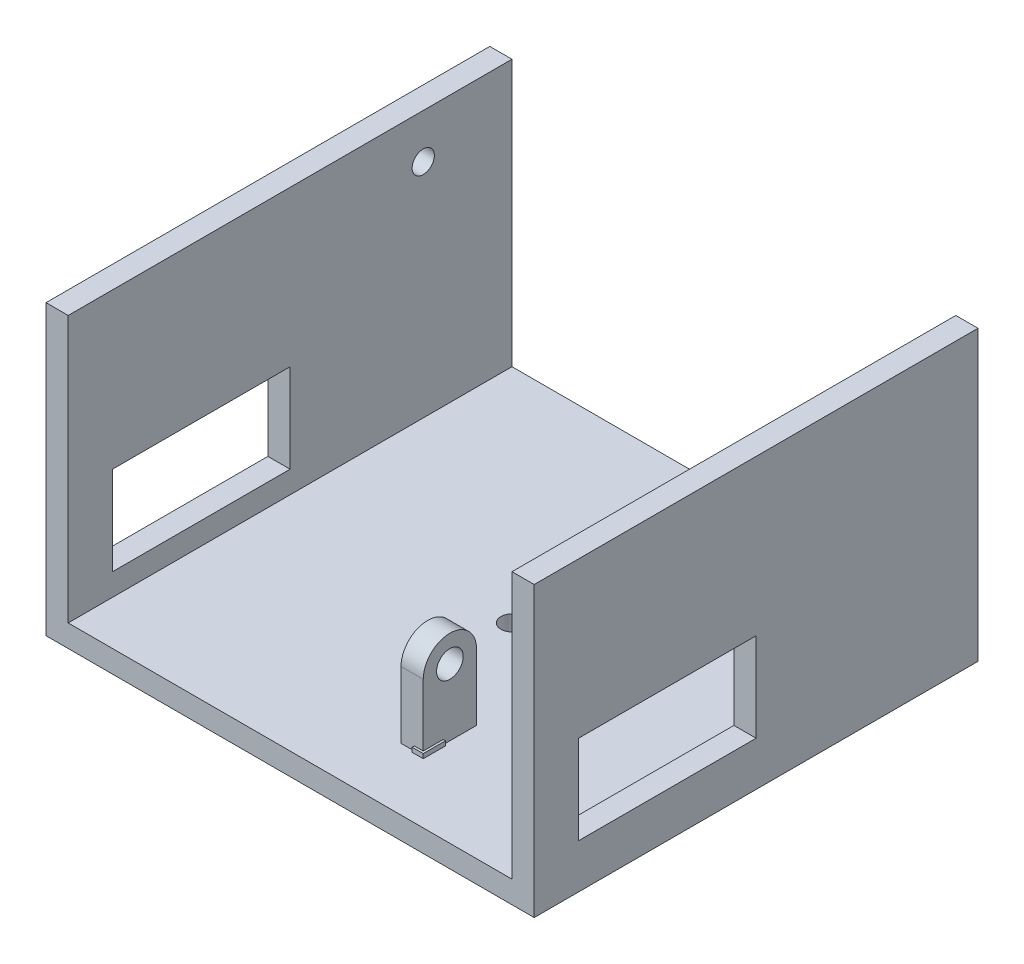
SolidWorks part; units mm, degrees
ref_plane "Front Plane" through (0, 0, 0) normal (0, 0, 1) x (1, 0, 0)
ref_plane "Top Plane" through (0, 0, 0) normal (0, 1, 0) x (1, 0, 0)
ref_plane "Right Plane" through (0, 0, 0) normal (1, 0, 0) x (0, 0, -1)
sketch "Sketch1" plane through (0, 0, 0) normal (0, 0, 1) x (1, 0, 0)
  line L0 (-50, 5) -> (50, 5)
  line L2 (55, 0) -> (-55, 0)
  line L7 (-55, 0) -> (-55, 65)
  line L8 (-55, 65) -> (-50, 65)
  line L9 (-50, 65) -> (-50, 5)
  line L10 (0, 0) -> (0, 425.5211) construction
  line L11 (50, 65) -> (50, 5)
  line L12 (55, 65) -> (50, 65)
  line L13 (55, 0) -> (55, 65)
  point P2 (0, 0)
  dimension "D1" = 60
  dimension "D2" = 5
  dimension "D3" = 110
  dimension "D4" = 5
extrude "Boss-Extrude2" add sketch "Sketch1" along normal blind 100
sketch "Sketch2" plane through (0, 5, 0) normal (0, 1, 0) x (1, 0, 0)
  line L0 (0, 0) -> (0, -100) construction
  line L1 (-29.4832, -50) -> (29.4832, -50) construction
  line L2 (50, -100) -> (-50, -100) construction
  circle A0 centre (0, -50) radius 2.5
  circle A4 centre (0, -30) radius 3
  point P9 (0, -50)
  dimension "D1" = 5
  dimension "D2" = 6
  dimension "D3" = 20
extrude "Cut-Extrude1" cut sketch "Sketch2" against normal blind 10
sketch "Sketch3" plane through (-55, 0, 0) normal (-1, 0, 0) x (0, 0, 1)
  line L0 (100, 0) -> (0, 0) construction
  line L1 (100, 65) -> (100, 0) construction
  line L2 (100, 65) -> (0, 65) construction
  line L3 (0, 65) -> (0, 0) construction
  circle A0 centre (80, 20) radius 2.5
  circle A1 centre (20, 55) radius 2.5
  dimension "D1" = 5
  dimension "D2" = 10
  dimension "D3" = 20
  dimension "D4" = 20
  dimension "D5" = 20
extrude "Cut-Extrude2" cut sketch "Sketch3" against normal blind 10
sketch "Sketch4" plane through (55, 0, 0) normal (1, 0, 0) x (0, 0, -1)
  line L0 (-100, 0) -> (0, 0) construction
  line L1 (-100, 0) -> (-100, 65) construction
  circle A0 centre (-80, 15) radius 2
  dimension "D1" = 4
  dimension "D2" = 15
  dimension "D3" = 20
extrude "Cut-Extrude3" cut sketch "Sketch4" against normal blind 10
sketch "Sketch5" plane through (-55, 0, 0) normal (-1, 0, 0) x (0, 0, 1)
  line L1 (90, 10) -> (50, 10)
  line L2 (90, 10) -> (90, 30)
  line L3 (90, 30) -> (50, 30)
  line L4 (50, 10) -> (50, 30)
  line L5 (90, 10) -> (50, 30) construction
  line L6 (90, 30) -> (50, 10) construction
  circle A0 centre (80, 20) radius 2.5 construction
  point P4 (70, 20)
  dimension "D3" = 10
  dimension "D4" = 10
  dimension "D1" = 20
  dimension "D2" = 40
extrude "Cut-Extrude4" cut sketch "Sketch5" against normal through all
sketch "Sketch6" plane through (0, 5, 0) normal (0, 1, 0) x (1, 0, 0)
  line L1 (11, -74) -> (16, -74)
  line L2 (11, -74) -> (11, -86)
  line L3 (11, -86) -> (16, -86)
  line L4 (16, -74) -> (16, -86)
  line L5 (11, -74) -> (16, -86) construction
  line L6 (11, -86) -> (16, -74) construction
  line L7 (50, -100) -> (50, 0) construction
  line L9 (50, -100) -> (-50, -100) construction
  point P0 (13.5, -80)
  dimension "D1" = 34
  dimension "D2" = 5
  dimension "D3" = 12
  dimension "D4" = 20
extrude "Boss-Extrude3" add sketch "Sketch6" along normal blind 15
sketch "Sketch8" plane through (11, 0, 0) normal (-1, 0, 0) x (0, 0, 1)
  line L1 (74, 20) -> (86, 20)
  arc A0 (74, 20) -> (86, 20) centre (80, 20) cw
extrude "Boss-Extrude4" add sketch "Sketch8" against normal up to surface (5 mm away) up to face at (16, 12.5, 80)
sketch "Sketch9" plane through (11, 0, 0) normal (-1, 0, 0) x (0, 0, 1)
  circle A0 centre (80, 20) radius 3
  dimension "D1" = 6
extrude "Cut-Extrude5" cut sketch "Sketch9" against normal blind 7
sketch "Sketch10" plane through (0, 5, 0) normal (0, 1, 0) x (1, 0, 0)
  line L0 (14, -86.5) -> (16.5, -86.5)
  line L1 (16.5, -86.5) -> (16.5, -81.5)
  line L2 (16.5, -81.5) -> (16, -81.5)
  line L4 (16, -81.5) -> (16, -86)
  line L5 (16, -86) -> (14, -86)
  line L7 (14, -86) -> (14, -86.5)
  line L8 (50, -100) -> (-50, -100) construction
  line L9 (50, -100) -> (50, 0) construction
  dimension "D1" = 5
  dimension "D2" = 0.5
  dimension "D3" = 2.5
  dimension "D4" = 13.5
  dimension "D5" = 33.5
extrude "Boss-Extrude5" add sketch "Sketch10" along normal blind 1
